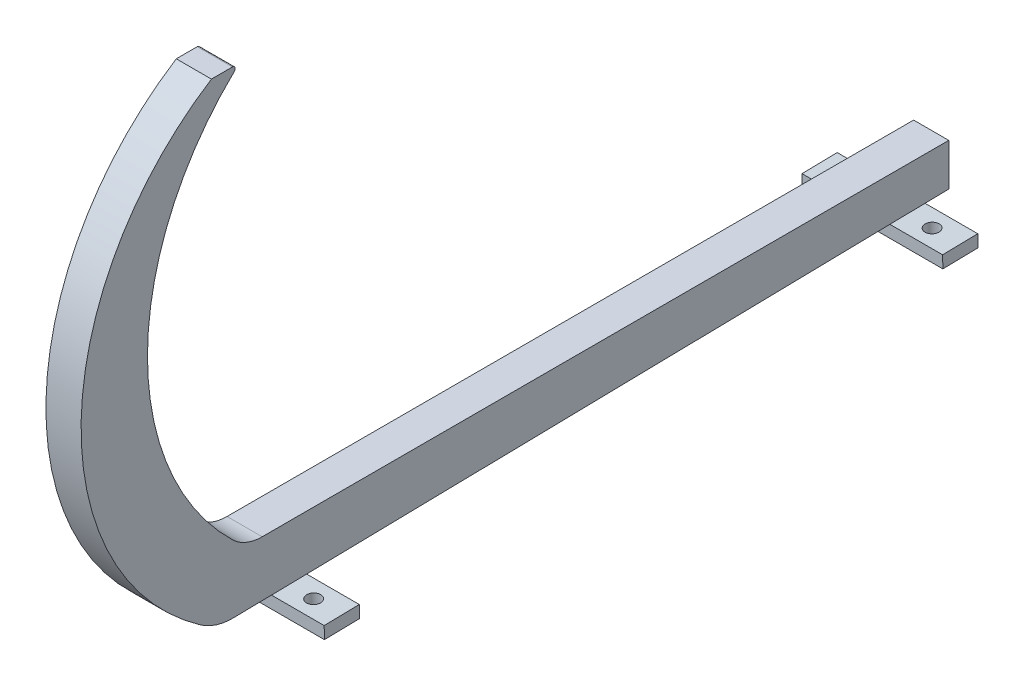
SolidWorks part; units mm, degrees
ref_plane "Front Plane" through (0, 0, 0) normal (0, 0, 1) x (1, 0, 0)
ref_plane "Top Plane" through (0, 0, 0) normal (0, 1, 0) x (1, 0, 0)
ref_plane "Right Plane" through (0, 0, 0) normal (1, 0, 0) x (0, 0, -1)
sketch "Sketch1" plane through (0, 0, 0) normal (1, 0, 0) x (0, 0, -1)
  line L0 (317.5, 0) -> (-302.7715, 0)
  line L1 (317.5, 0) -> (317.5, -38.1)
  line L2 (317.5, -38.1) -> (-328.114, -50.501)
  line L3 (-348.6238, 381) -> (-323.2238, 381)
  arc A0 (-329.3076, 10.7606) -> (-323.2238, 381) centre (-152.4, 193.0233) cw
  arc A1 (-358.2667, -41.2957) -> (-348.6238, 381) centre (-212.3815, 166.631) cw
  arc A2 (-302.7715, 0) -> (-329.3076, 10.7606) centre (-302.7715, 38.1) cw
  arc A3 (-328.114, -50.501) -> (-358.2667, -41.2957) centre (-329.0896, 0.2897) cw
  point P11 (-317.5, 0)
  point P14 (-343.6817, -50.8)
  dimension "D5" = 254
  dimension "D9" = 254
  dimension "D11" = 38.1
  dimension "D12" = 50.8
  dimension "D1" = 38.1
  dimension "D2" = 635
  dimension "D3" = 50.8
  dimension "D4" = 57.15
  dimension "D6" = 152.4
  dimension "D7" = 317.5
  dimension "D8" = 381
  dimension "D10" = 25.4
extrude "Boss-Extrude1" add sketch "Sketch1" along normal mid plane 31.75
sketch "Sketch2" plane through (0, -44.1822, -0.8487) normal (0, -0.9998, -0.0192) x (1, 0, 0)
  line L0 (0, 329.0234) -> (0, 0) construction
  line L1 (15.875, 329.0234) -> (-15.875, 329.0234) construction
  line L2 (0, 0) -> (-225.3719, 0) construction
  line L3 (-63.5, 295.275) -> (63.5, 295.275)
  line L4 (-63.5, 295.275) -> (-63.5, 263.525)
  line L5 (-63.5, 263.525) -> (63.5, 263.525)
  line L6 (63.5, 295.275) -> (63.5, 263.525)
  line L7 (-63.5, 295.275) -> (63.5, 263.525) construction
  line L8 (-63.5, 263.525) -> (63.5, 295.275) construction
  line L9 (-63.5, -263.525) -> (63.5, -295.275) construction
  line L10 (-63.5, -295.275) -> (63.5, -263.525) construction
  line L11 (63.5, -295.275) -> (63.5, -263.525)
  line L12 (-63.5, -263.525) -> (63.5, -263.525)
  line L13 (-63.5, -295.275) -> (-63.5, -263.525)
  line L14 (-63.5, -295.275) -> (63.5, -295.275)
  circle A0 centre (38.1, 279.4) radius 6.35
  circle A1 centre (-38.1, 279.4) radius 6.35
  circle A2 centre (-38.1, -279.4) radius 6.35
  circle A3 centre (38.1, -279.4) radius 6.35
  point P5 (0, 279.4)
  point P23 (0, -279.4)
  dimension "D4" = 12.7
  dimension "D1" = 31.75
  dimension "D2" = 127
  dimension "D3" = 279.4
  dimension "D5" = 76.2
  dimension "D6" = 38.1
extrude "Boss-Extrude2" add sketch "Sketch2" along normal blind 11.176
fillet "Fillet1" radius 2.54 1 edges at (0, 381, 323.2238)
